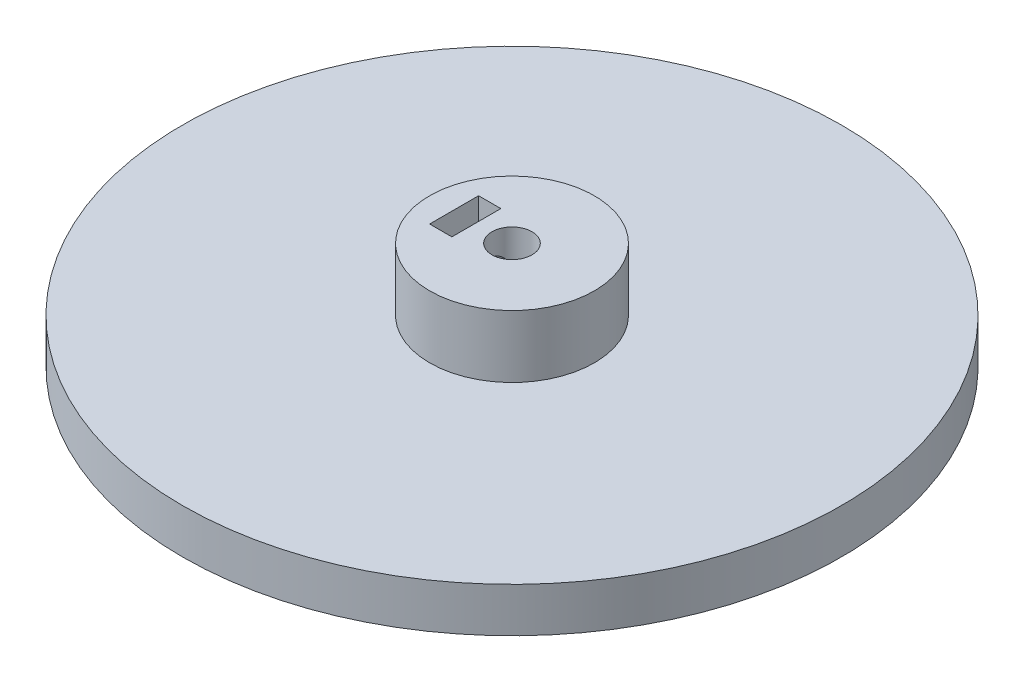
SolidWorks part; units mm, degrees
material "Custom Plastic"
ref_plane "Front Plane" through (0, 0, 0) normal (0, 0, 1) x (1, 0, 0)
ref_plane "Top Plane" through (0, 0, 0) normal (0, 1, 0) x (1, 0, 0)
ref_plane "Right Plane" through (0, 0, 0) normal (1, 0, 0) x (0, 0, -1)
sketch "Sketch1" plane through (0, 0, 0) normal (0, 1, 0) x (1, 0, 0)
  circle A0 centre (0, 0) radius 37
  dimension "D1" = 74
extrude "Boss-Extrude1" add sketch "Sketch1" along normal blind 5
sketch "Sketch2" plane through (0, 5, 0) normal (0, 1, 0) x (1, 0, 0)
  circle A0 centre (0, 0) radius 2.25
  circle A1 centre (0, 0) radius 9.25
  dimension "D1" = 4.5
  dimension "D2" = 7
extrude "Boss-Extrude2" add sketch "Sketch2" along normal blind 7
ref_plane "Plane1" through (-9.25, 0, 0) normal (-1, 0, 0) x (0, 0, 1)
hole_wizard "Ø1.0mm Dowel Hole1" positions "Sketch3" profile "Sketch4" hole size "Ø1.0" standard "ANSI Metric"
sketch "Sketch3" plane through (-9.25, 0, 0) normal (-1, 0, 0) x (0, 0, 1)
  line L0 (0, 12) -> (0, 5) construction
  line L1 (9.25, 12) -> (-9.25, 12) construction
  line L2 (37, 5) -> (-37, 5) construction
  point P0 (0, 8)
  dimension "D1" = 3
sketch "Sketch4" plane through (-9.25, 8, 0) normal (0, 1, 0) x (0, 0, 1)
  line L0 (0, 0) -> (0, 8)
  line L1 (0, 8) -> (1.5, 8)
  line L2 (1.5, 8) -> (1.5, 0)
  line L5 (1.5, 0) -> (0, 0)
  line L10 (0, 8) -> (-1.5, 8) construction
  line L11 (0, -6.35) -> (0, 107.95) construction
  dimension "Hole Dia." = 3
  dimension "Hole Depth" = 8
  dimension "Drill Angle" = 180
sketch "Sketch5" plane through (0, 5, 0) normal (0, 1, 0) x (1, 0, 0)
  circle A0 centre (0, 0) radius 2.25 construction
  circle A1 centre (0, 0) radius 2.25
extrude "Cut-Extrude1" cut sketch "Sketch5" against normal blind 2
ref_plane "Plane2" through (-6.5, 0, 0) normal (1, 0, 0) x (0, 0, -1)
sketch "Sketch6" plane through (-6.5, 0, 0) normal (1, 0, 0) x (0, 0, -1)
  line L0 (2.25, 12) -> (-2.25, 12) construction
  line L2 (-2.75, 12) -> (-2.75, 6.4123)
  line L3 (-2.75, 6.4123) -> (0, 4.8246)
  line L4 (0, 4.8246) -> (2.75, 6.4123)
  line L5 (2.75, 6.4123) -> (2.75, 12)
  line L7 (1.5915, 10.2566) -> (0.9665, 10.6174) [skipped]
  line L8 (-1.5915, 10.2566) -> (-2.2165, 9.8957) [skipped]
  line L9 (9.25, 12) -> (-9.25, 12) construction
  line L10 (-2.75, 12) -> (2.75, 12)
  circle A0 centre (0, 8) radius 2.75 construction
  dimension "D1" = 5.5
extrude "Cut-Extrude2" cut sketch "Sketch6" along normal blind 2.5
